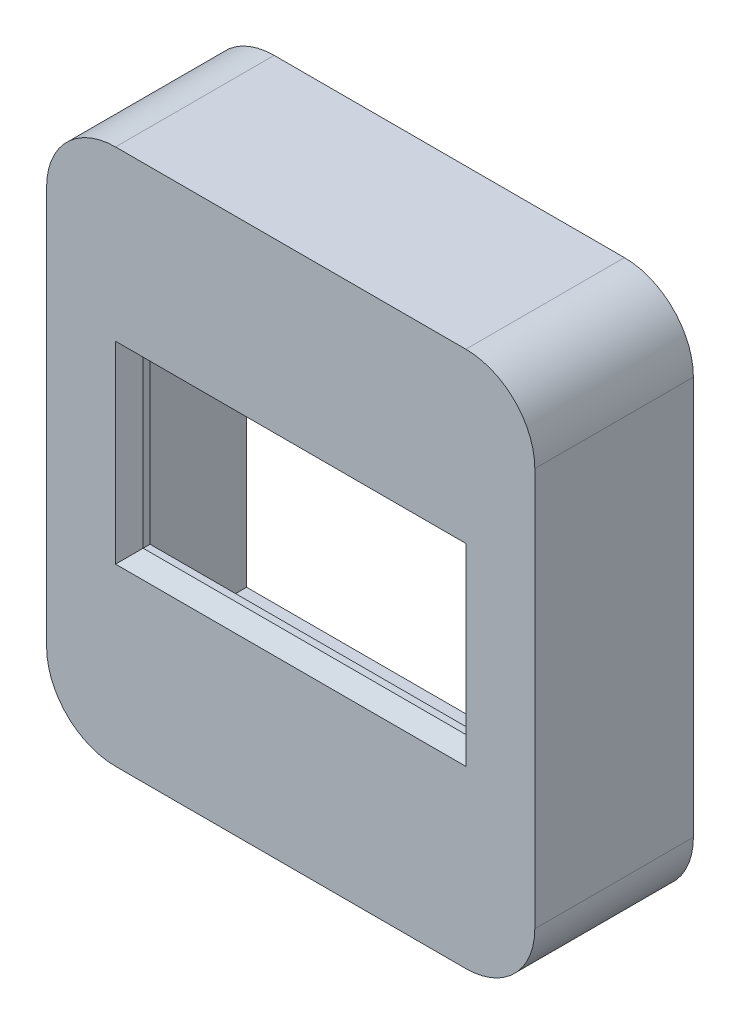
SolidWorks part; units mm, degrees
ref_plane "Front Plane" through (0, 0, 0) normal (0, 0, 1) x (1, 0, 0)
ref_plane "Top Plane" through (0, 0, 0) normal (0, 1, 0) x (1, 0, 0)
ref_plane "Right Plane" through (0, 0, 0) normal (1, 0, 0) x (0, 0, -1)
sketch "Sketch2" plane through (0, 0, 0) normal (0, 0, 1) x (1, 0, 0)
  line L0 (12.35, 1.35) -> (-12.35, 1.35) construction
  line L1 (12.35, -5.9) -> (12.35, 8.6) construction
  line L2 (-12.35, 8.6) -> (-12.35, -5.9) construction
  line L3 (7.3, -13.1) -> (12.7, -13.1) construction
  line L4 (17.7, -18.1) -> (-17.7, -18.1)
  line L5 (17.7, -18.1) -> (17.7, 20.8)
  line L6 (17.7, 20.8) -> (-17.7, 20.8)
  line L7 (-17.7, -18.1) -> (-17.7, 20.8)
  line L8 (17.7, -18.1) -> (-17.7, 20.8) construction
  line L9 (17.7, 20.8) -> (-17.7, -18.1) construction
  line L10 (12.7, -13.1) -> (12.7, 13.1) construction
  point P6 (0, 1.35)
  dimension "D1" = 5
  dimension "D2" = 5
extrude "Boss-Extrude1" add sketch "Sketch2" along normal blind 1.5
sketch "Sketch4" plane through (0, 0, 0) normal (0, 0, -1) x (-1, 0, 0)
  line L1 (11.7, 7.6) -> (-11.7, 7.6)
  line L2 (11.7, 7.6) -> (11.7, -4.4)
  line L3 (11.7, -4.4) -> (-11.7, -4.4)
  line L4 (-11.7, 7.6) -> (-11.7, -4.4)
  line L5 (-12.35, -5.4) -> (12.35, -5.4) construction
  line L6 (-12.35, 8.6) -> (12.35, 8.6) construction
  line L9 (12.7, -13.1) -> (12.7, 13.1) construction
  line L11 (-12.7, -13.1) -> (-12.7, 13.1) construction
  dimension "D1" = 1
  dimension "D2" = 1
  dimension "D3" = 1
  dimension "D4" = 1
extrude "Cut-Extrude1" cut sketch "Sketch4" against normal blind 1.5
sketch "Sketch5" plane through (0, 0, 0) normal (0, 0, -1) x (-1, 0, 0)
  line L0 (12.7, -13.1) -> (7.3, -13.1) construction
  line L1 (14.7, -13.6) -> (-14.7, -13.6)
  line L2 (14.7, -13.6) -> (14.7, 13.6)
  line L3 (14.7, 13.6) -> (-14.7, 13.6)
  line L4 (-14.7, -13.6) -> (-14.7, 13.6)
  line L6 (12.7, 13.1) -> (-12.7, 13.1) construction
  line L7 (-12.7, 13.1) -> (-12.7, -13.1) construction
  line L8 (12.7, -13.1) -> (12.7, 13.1) construction
  line M9 (17.7, -18.1) -> (17.7, 20.8)
  line M10 (17.7, 20.8) -> (-17.7, 20.8)
  line M11 (-17.7, 20.8) -> (-17.7, -18.1)
  line M12 (-17.7, -18.1) -> (17.7, -18.1)
  dimension "D1" = 0.5
  dimension "D2" = 0.5
  dimension "D3" = 2
  dimension "D4" = 2
extrude "Boss-Extrude2" add sketch "Sketch5" along normal blind 10 contours L1 L4 L3 L2 M12 M9 M10 M11
fillet "Fillet1" radius 5 4 edges at (-17.7, -18.1, -4.25) (-17.7, 20.8, -4.25) (17.7, 20.8, -4.25) (17.7, -18.1, -4.25)
sketch "Sketch7" plane through (0, 0, -10) normal (0, 0, -1) x (-1, 0, 0)
  line L0 (14.7, 13.6) -> (-14.7, 13.6) construction
  line L1 (7.08, 13.6) -> (-7.08, 13.6)
  line L2 (7.08, 13.6) -> (7.08, 18.8)
  line L3 (7.08, 18.8) -> (-7.08, 18.8)
  line L4 (-7.08, 13.6) -> (-7.08, 18.8)
  line L5 (-5.08, 12.6) -> (-5.08, 11.06) construction
  line L6 (5.08, 11.06) -> (5.08, 12.6) construction
  line L7 (12.7, 20.8) -> (-12.7, 20.8) construction
  dimension "D1" = 2
  dimension "D2" = 2
  dimension "D3" = 2
extrude "Cut-Extrude2" cut sketch "Sketch7" against normal up to surface (10 mm away) up to face at (0, 1.6, 0)
sketch "Sketch8" plane through (0, 0, 0) normal (0, 0, -1) x (-1, 0, 0)
  line L0 (-12.35, -8.4) -> (12.35, -8.4) construction
  line L1 (14.7, -13.6) -> (7.7, -13.6)
  line L2 (14.7, -13.6) -> (14.7, -8.4)
  line L3 (14.7, -8.4) -> (7.7, -8.4)
  line L4 (7.7, -13.6) -> (7.7, -8.4)
  line L5 (0, -13.6) -> (0, 18.8) construction
  line L6 (14.7, -13.6) -> (-14.7, -13.6) construction
  line L7 (7.08, 18.8) -> (-7.08, 18.8) construction
  line L8 (14.7, 0) -> (-14.7, 0) construction
  line L9 (14.7, -13.6) -> (14.7, 13.6) construction
  line L10 (-14.7, -13.6) -> (-14.7, 13.6) construction
  line L11 (14.7, 8.4) -> (7.7, 8.4)
  line L12 (7.7, 13.6) -> (7.7, 8.4)
  line L13 (14.7, 13.6) -> (7.7, 13.6)
  line L14 (14.7, 13.6) -> (14.7, 8.4)
  line L15 (-14.7, 13.6) -> (-14.7, 8.4)
  line L16 (-14.7, 13.6) -> (-7.7, 13.6)
  line L17 (-7.7, 13.6) -> (-7.7, 8.4)
  line L18 (-14.7, 8.4) -> (-7.7, 8.4)
  line L19 (-14.7, -8.4) -> (-7.7, -8.4)
  line L20 (-7.7, -13.6) -> (-7.7, -8.4)
  line L21 (-14.7, -13.6) -> (-7.7, -13.6)
  line L22 (-14.7, -13.6) -> (-14.7, -8.4)
  dimension "D1" = 7
extrude "Boss-Extrude3" add sketch "Sketch8" along normal up to surface (1.8 mm away)
sketch "Sketch9" plane through (-14.7, 0, 0) normal (1, 0, 0) x (0, 0, -1)
  line L0 (3.5, 13.6) -> (10, 12.6)
  line L1 (10, 13.6) -> (1.8, 13.6) construction
  line L2 (10, -13.6) -> (10, 13.6) construction
  line L3 (10, 12.6) -> (10, 13.6)
  line L4 (10, 13.6) -> (3.5, 13.6)
  dimension "D1" = 1
  dimension "D2" = 6.5
extrude "Boss-Extrude4" add sketch "Sketch9" along normal up to vertex (7.62 mm away) up to point (-7.08, 13.6, -10)
mirror "Mirror1" about plane through (0, 0, 0) normal (1, 0, 0) of "Boss-Extrude4"
sketch "Sketch10" plane through (0, 0, -1.8) normal (0, 0, -1) x (-1, 0, 0)
  line L0 (14.7, -13.6) -> (14.7, 12.6) construction
  line L1 (7.7, -8.4) -> (14.7, -8.4) construction
  circle A0 centre (10.2, -12) radius 0.95
  dimension "D1" = 1.9
  dimension "D2" = 4.5
  dimension "D3" = 3.6
extrude "Boss-Extrude5" add sketch "Sketch10" along normal offset from surface (2 mm away) 0.5
mirror "Mirror2" about plane through (0, 0, 0) normal (1, 0, 0) of "Boss-Extrude5"
chamfer "Chamfer1" distance 1 angle 45 4 edges at (0, 7.6, 1.5) (11.7, 1.6, 1.5) (0, -4.4, 1.5) (-11.7, 1.6, 1.5)
